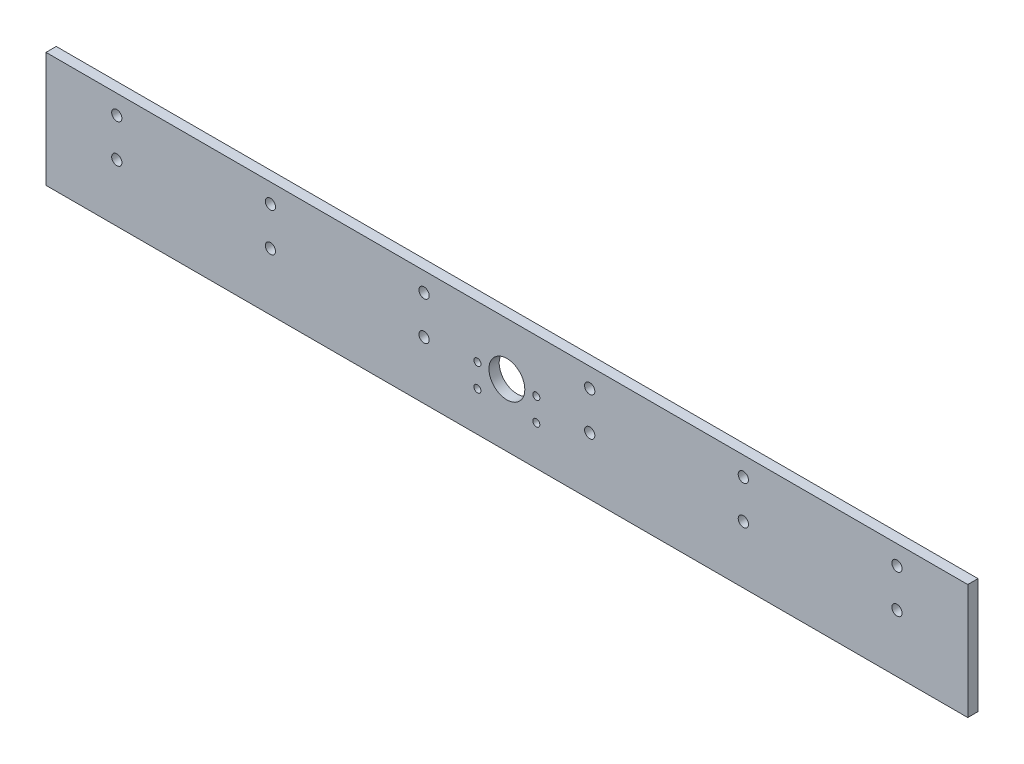
SolidWorks part; units mm, degrees
ref_plane "Plan de face" through (0, 0, 0) normal (0, 0, 1) x (1, 0, 0)
ref_plane "Plan de dessus" through (0, 0, 0) normal (0, 1, 0) x (1, 0, 0)
ref_plane "Plan de droite" through (0, 0, 0) normal (1, 0, 0) x (0, 0, -1)
sketch "Esquisse1" plane through (0, 0, 0) normal (0, 0, 1) x (1, 0, 0)
  line L0 (317, 48.92) -> (363, 48.92) construction
  line L1 (0, 0) -> (680, 0)
  line L2 (0, 0) -> (0, 90)
  line L3 (0, 90) -> (680, 90)
  line L4 (680, 0) -> (680, 90)
  line L5 (340, 90) -> (340, -21.5047) construction
  circle A0 centre (317, 48.92) radius 2.75
  circle A1 centre (363, 48.92) radius 2.75
  circle A2 centre (363, 30.92) radius 2.75
  circle A3 centre (317, 30.92) radius 2.75
  circle A4 centre (340, 48.92) radius 14
  circle A5 centre (35.3, 75) radius 4
  circle A6 centre (35.3, 45) radius 4
  circle A7 centre (644.7, 45) radius 4
  circle A8 centre (644.7, 75) radius 4
  circle A9 centre (155.3, 75) radius 4
  circle A10 centre (155.3, 45) radius 4
  circle A11 centre (275.3, 75) radius 4
  circle A12 centre (275.3, 45) radius 4
  circle A13 centre (404.7, 45) radius 4
  circle A14 centre (404.7, 75) radius 4
  circle A15 centre (524.7, 45) radius 4
  circle A16 centre (524.7, 75) radius 4
  dimension "D4" = 5.5
  dimension "D8" = 28
  dimension "D9" = 23
  dimension "D10" = 35.3
  dimension "D11" = 30
  dimension "D12" = 8
  dimension "D13" = 8
  dimension "D14" = 35.3
  dimension "D15" = 15
  dimension "D1" = 680
  dimension "D2" = 90
  dimension "D3" = 317
  dimension "D5" = 41.08
  dimension "D6" = 2
  dimension "D7" = 2
  dimension "D16" = 3
extrude "Boss.-Extru.1" add sketch "Esquisse1" along normal blind 8
sketch "Esquisse2" plane through (0, 0, 0) normal (-1, 0, 0) x (0, 0, 1)
  line L1 (0, 90) -> (8, 90)
  line L2 (0, 90) -> (0, 0)
  line L3 (0, 0) -> (8, 0)
  line L4 (8, 90) -> (8, 0)
extrude "Boss.-Extru.2" add sketch "Esquisse2" along normal blind 20
sketch "Esquisse3" plane through (680, 0, 0) normal (1, 0, 0) x (0, 0, -1)
  line L1 (-8, 90) -> (0, 90)
  line L2 (-8, 90) -> (-8, 0)
  line L3 (-8, 0) -> (0, 0)
  line L4 (0, 90) -> (0, 0)
extrude "Boss.-Extru.3" add sketch "Esquisse3" along normal blind 20
